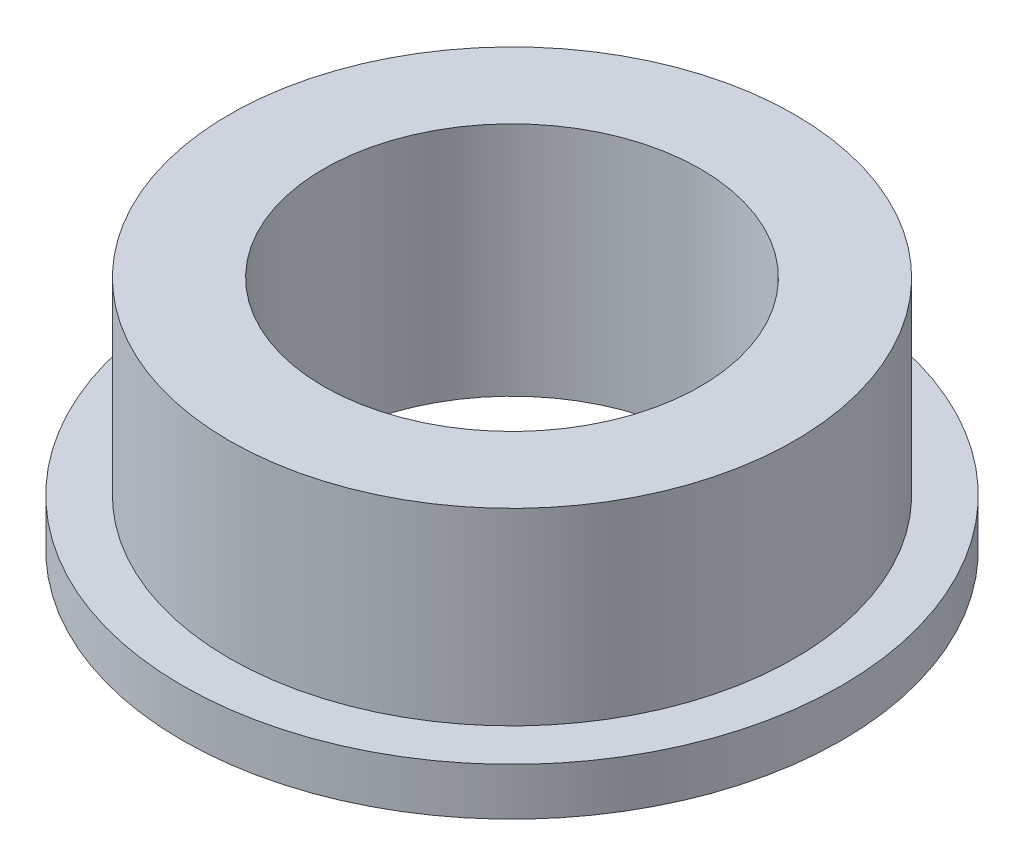
SolidWorks part; units mm, degrees
ref_plane "Front Plane" through (0, 0, 0) normal (0, 0, 1) x (1, 0, 0)
ref_plane "Top Plane" through (0, 0, 0) normal (0, 1, 0) x (1, 0, 0)
ref_plane "Right Plane" through (0, 0, 0) normal (1, 0, 0) x (0, 0, -1)
sketch "Sketch1" plane through (0, 0, 0) normal (0, 1, 0) x (1, 0, 0)
  circle A0 centre (0, 0) radius 11.1125
  circle A1 centre (0, 0) radius 6.35
  dimension "D1" = 22.225
  dimension "D2" = 12.7
extrude "Boss-Extrude1" add sketch "Sketch1" along normal blind 1.6002
sketch "Sketch2" plane through (0, 1.6002, 0) normal (0, 1, 0) x (1, 0, 0)
  circle A0 centre (0, 0) radius 9.525
  circle A1 centre (0, 0) radius 6.35
  circle A2 centre (0, 0) radius 6.35 construction
  dimension "D1" = 19.05
extrude "Boss-Extrude2" add sketch "Sketch2" along normal blind 6.35
